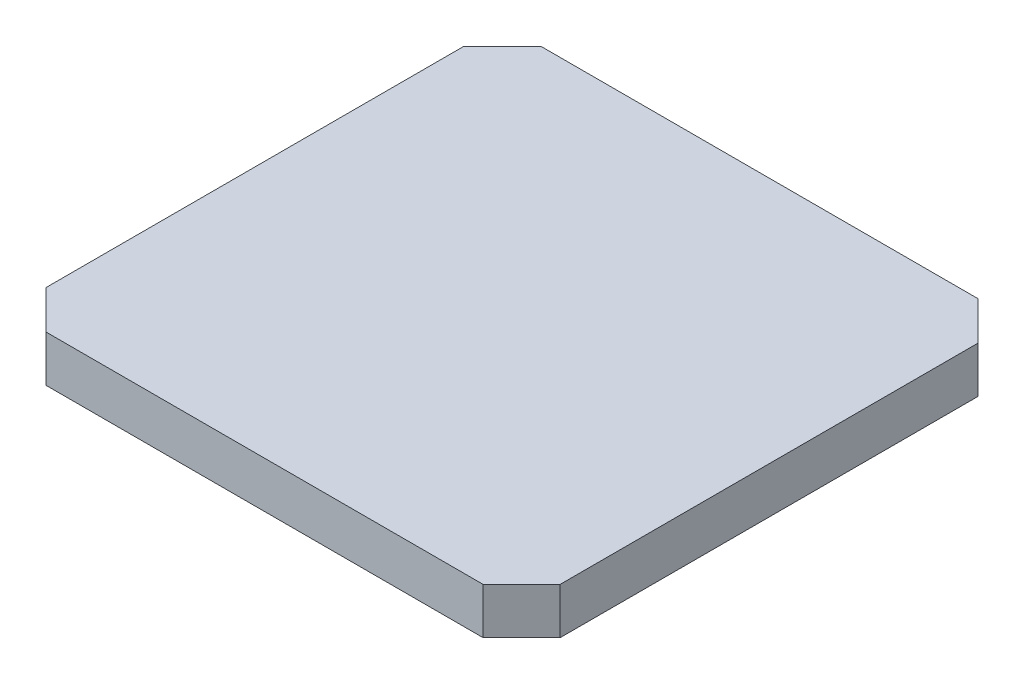
SolidWorks part; units mm, degrees
ref_plane "Front Plane" through (0, 0, 0) normal (0, 0, 1) x (1, 0, 0)
ref_plane "Top Plane" through (0, 0, 0) normal (0, 1, 0) x (1, 0, 0)
ref_plane "Right Plane" through (0, 0, 0) normal (1, 0, 0) x (0, 0, -1)
sketch "Sketch1" plane through (0, 0, 0) normal (0, 1, 0) x (1, 0, 0)
  line L0 (-49.3, 41.6048) -> (-43.2, 47.7048)
  line L1 (-34, -47.5952) -> (34, -47.5952)
  line L2 (-49.3, -37.9952) -> (-49.3, 41.6048)
  line L3 (-43.2, 47.7048) -> (-35.5, 47.7048)
  line L4 (49.3, -37.9952) -> (49.3, 41.6048)
  line L5 (-49.3, -47.5952) -> (49.2706, 47.5669) construction
  line L6 (-49.3548, 47.6481) -> (49.3, -47.5952) construction
  line L7 (0, 0) -> (0, 47.7048) construction
  line L8 (49.3, 41.6048) -> (43.2, 47.7048)
  line L9 (-46.8, -44.0952) -> (-46.8, -38.9952)
  line L10 (-45.8, -45.0952) -> (-35, -45.0952)
  line L11 (46.8, -44.0952) -> (46.8, -38.9952)
  line L12 (-49.3, -37.9952) -> (-47.8, -37.9952)
  line L13 (-34, -47.5952) -> (-34, -46.0952)
  line L14 (34, -47.5952) -> (34, -46.0952)
  line L15 (49.3, -37.9952) -> (47.8, -37.9952)
  line L16 (35, -45.0952) -> (45.8, -45.0952)
  line L17 (-46.8, -45.0952) -> (-46.8, 41.6048) construction
  line L18 (46.8, -45.0952) -> (46.8, 41.6048) construction
  line L19 (-34.5, 44.0048) -> (-4.5, 44.0048)
  line L20 (-46.8, -45.0952) -> (46.8, -45.0952) construction
  line L21 (-49.3, -47.5952) -> (49.3, -47.5952) construction
  line L22 (-49.3, -47.5952) -> (-49.3, 41.6048) construction
  line L23 (49.3, -47.5952) -> (49.3, 41.6048) construction
  line L24 (-35.5, 47.7048) -> (-35.5, 45.0048)
  line L25 (-3.5, 47.7048) -> (-3.5, 45.0048)
  line L26 (-3.5, 47.7048) -> (43.2, 47.7048)
  line L27 (-43.2, 44.0048) -> (43.2, 44.0048) construction
  line L28 (21.27, 40.7348) -> (23.81, 40.7348) construction
  line L29 (-43.2, 47.7048) -> (43.2, 47.7048) construction
  line L30 (28.67, 40.7348) -> (31.21, 40.7348) construction
  line L31 (28.67, 40.7348) -> (28.67, 43.2748) construction
  line L32 (28.67, 43.2748) -> (31.21, 43.2748) construction
  line L33 (31.21, 40.7348) -> (31.21, 43.2748) construction
  line L34 (28.67, 40.7348) -> (31.21, 43.2748) construction
  line L35 (28.67, 43.2748) -> (31.21, 40.7348) construction
  line L36 (21.27, 40.7348) -> (21.27, 43.2748) construction
  line L37 (21.27, 43.2748) -> (23.81, 43.2748) construction
  line L38 (23.81, 40.7348) -> (23.81, 43.2748) construction
  line L39 (21.27, 40.7348) -> (23.81, 43.2748) construction
  line L40 (21.27, 43.2748) -> (23.81, 40.7348) construction
  line L41 (13.87, 40.7348) -> (16.41, 40.7348) construction
  line L42 (13.87, 40.7348) -> (13.87, 43.2748) construction
  line L43 (13.87, 43.2748) -> (16.41, 43.2748) construction
  line L44 (16.41, 40.7348) -> (16.41, 43.2748) construction
  line L45 (13.87, 40.7348) -> (16.41, 43.2748) construction
  line L46 (13.87, 43.2748) -> (16.41, 40.7348) construction
  arc A0 (47.8, -37.9952) -> (46.8, -38.9952) centre (47.8, -38.9952) ccw
  arc A1 (35, -45.0952) -> (34, -46.0952) centre (35, -46.0952) ccw
  arc A2 (-34, -46.0952) -> (-35, -45.0952) centre (-35, -46.0952) ccw
  arc A3 (-46.8, -38.9952) -> (-47.8, -37.9952) centre (-47.8, -38.9952) ccw
  arc A4 (46.8, -44.0952) -> (45.8, -45.0952) centre (45.8, -44.0952) cw
  arc A5 (-45.8, -45.0952) -> (-46.8, -44.0952) centre (-45.8, -44.0952) cw
  arc A6 (-4.5, 44.0048) -> (-3.5, 45.0048) centre (-4.5, 45.0048) ccw
  arc A7 (-34.5, 44.0048) -> (-35.5, 45.0048) centre (-34.5, 45.0048) cw
  circle A8 centre (-33.77, 39.7448) radius 0.4
  circle A9 centre (-5.22, 39.7448) radius 0.4
  circle A10 centre (29.94, 42.0048) radius 0.2125
  circle A11 centre (28.67, 43.2748) radius 0.2125
  circle A12 centre (31.21, 43.2748) radius 0.2125
  circle A13 centre (31.21, 40.7348) radius 0.2125
  circle A14 centre (28.67, 40.7348) radius 0.2125
  circle A15 centre (22.54, 42.0048) radius 0.2125
  circle A16 centre (21.27, 43.2748) radius 0.2125
  circle A17 centre (23.81, 43.2748) radius 0.2125
  circle A18 centre (23.81, 40.7348) radius 0.2125
  circle A19 centre (21.27, 40.7348) radius 0.2125
  circle A20 centre (15.14, 42.0048) radius 0.2125
  circle A21 centre (13.87, 43.2748) radius 0.2125
  circle A22 centre (16.41, 43.2748) radius 0.2125
  circle A23 centre (16.41, 40.7348) radius 0.2125
  circle A24 centre (13.87, 40.7348) radius 0.2125
  point P0 (0, 0)
  point P26 (46.8, -37.9952)
  point P29 (34, -45.0952)
  point P32 (-34, -45.0952)
  point P35 (-46.8, -37.9952)
  dimension "D9" = 1
  dimension "D10" = 1
  dimension "D11" = 3.7
  dimension "D14" = 1
  dimension "D16" = 0.8
  dimension "D18" = 7.96
  dimension "D19" = 9.43
  dimension "D20" = 28.55
  dimension "D21" = 0.425
  dimension "D22" = 1.27
  dimension "D1" = 47.7048
  dimension "D2" = 98.6
  dimension "D3" = 6.1
  dimension "D4" = 6.1
  dimension "D5" = 95.3
  dimension "D6" = 2.5
  dimension "D7" = 85.7
  dimension "D8" = 15.3
  dimension "D12" = 13.8
  dimension "D13" = 32
  dimension "D15" = 137.1279
  dimension "D17" = 7.96
  dimension "D23" = 5.7
  dimension "D24" = 13.26
  dimension "D25" = 1.27
  dimension "D27" = 5.7
  dimension "D28" = 7.4
  dimension "D26" = 3
sketch "Sketch4" plane through (0, 0, 0) normal (0, 1, 0) x (1, 0, 0)
  line L0 (-46.75, 38) -> (-39.75, 45)
  line L1 (-39.75, -45) -> (39.75, -45)
  line L2 (-46.75, -38) -> (-46.75, 38)
  line L3 (-39.75, 45) -> (39.75, 45)
  line L4 (46.75, -38) -> (46.75, 38)
  line L5 (-46.75, -45) -> (46.75, 45) construction
  line L6 (-46.75, 45) -> (46.75, -45) construction
  line L7 (39.75, 45) -> (46.75, 38)
  line L8 (-39.75, -45) -> (-46.75, -38)
  line L9 (39.75, -45) -> (46.75, -38)
  point P0 (0, 0)
  dimension "D1" = 93.5
  dimension "D2" = 90
extrude "Boss-Extrude1" add sketch "Sketch4" along normal blind 8.4
